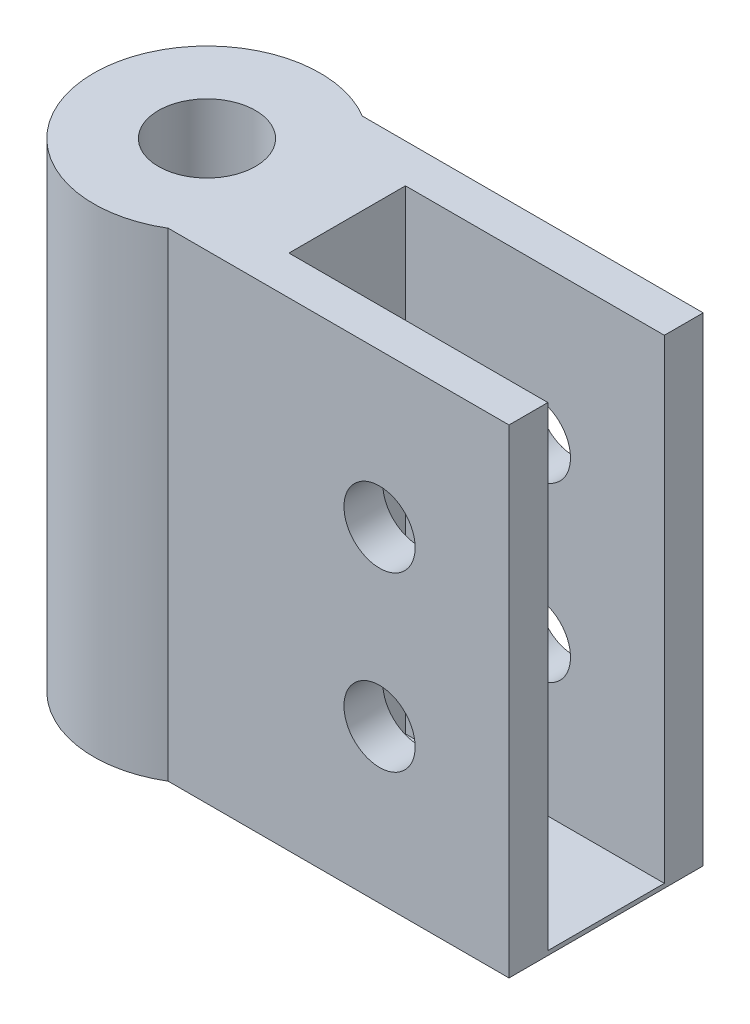
SolidWorks part; units mm, degrees
ref_plane "前视基准面" through (0, 0, 0) normal (0, 0, 1) x (1, 0, 0)
ref_plane "上视基准面" through (0, 0, 0) normal (0, 1, 0) x (1, 0, 0)
ref_plane "右视基准面" through (0, 0, 0) normal (1, 0, 0) x (0, 0, -1)
sketch "草图1" plane through (0, 0, 0) normal (0, 1, 0) x (1, 0, 0)
  circle A0 centre (0, 0) radius 2.25
  circle A1 centre (0, 0) radius 5.25
  dimension "D1" = 4.5
  dimension "D2" = 3
extrude "凸台-拉伸1" add sketch "草图1" along normal blind 22.2
sketch "草图2" plane through (0, 22.2, 0) normal (0, 1, 0) x (1, 0, 0)
  line L1 (18.5, -4.5) -> (2.5, -4.5)
  line L2 (18.5, -4.5) -> (18.5, 4.5)
  line L3 (18.5, 4.5) -> (2.5, 4.5)
  line L4 (2.5, -4.5) -> (2.5, 4.5)
  line L5 (18.5, -4.5) -> (2.5, 4.5) construction
  line L6 (18.5, 4.5) -> (2.5, -4.5) construction
  point P0 (10.5, 0)
  dimension "D1" = 10.5
  dimension "D2" = 16
  dimension "D3" = 9
extrude "凸台-拉伸2" add sketch "草图2" against normal up to surface (22.2 mm away) up to face at (0, 0, 5.25)
sketch "草图3" plane through (0, 22.2, 0) normal (0, 1, 0) x (1, 0, 0)
  line L0 (18.5, -4.5) -> (18.5, 4.5) construction
  line L1 (6.5, -2.7) -> (18.5, -2.7)
  line L2 (6.5, -2.7) -> (6.5, 2.7)
  line L3 (6.5, 2.7) -> (18.5, 2.7)
  line L4 (18.5, -2.7) -> (18.5, 2.7)
  line L5 (6.5, -2.7) -> (18.5, 2.7) construction
  line L6 (6.5, 2.7) -> (18.5, -2.7) construction
  point P0 (12.5, 0)
  dimension "D1" = 5.4
  dimension "D2" = 12
extrude "切除-拉伸1" cut sketch "草图3" against normal blind 22
sketch "草图4" plane through (0, 0, 4.5) normal (0, 0, 1) x (1, 0, 0)
  line L0 (6.5, 0.2) -> (6.5, 22.2) construction
  line L1 (6.5, 0.2) -> (6.5, 22.2) construction
  line L3 (18.5, 11.1) -> (2.7042, 11.1) construction
  line L4 (18.5, 0) -> (18.5, 22.2) construction
  line L5 (2.7042, 0) -> (2.7042, 22.2) construction
  circle A0 centre (12.5, 15.1) radius 1.65
  circle A2 centre (12.5, 7.1) radius 1.65
  dimension "D1" = 8
  dimension "D2" = 3.3
  dimension "D4" = 6
extrude "切除-拉伸2" cut sketch "草图4" against normal blind 22
